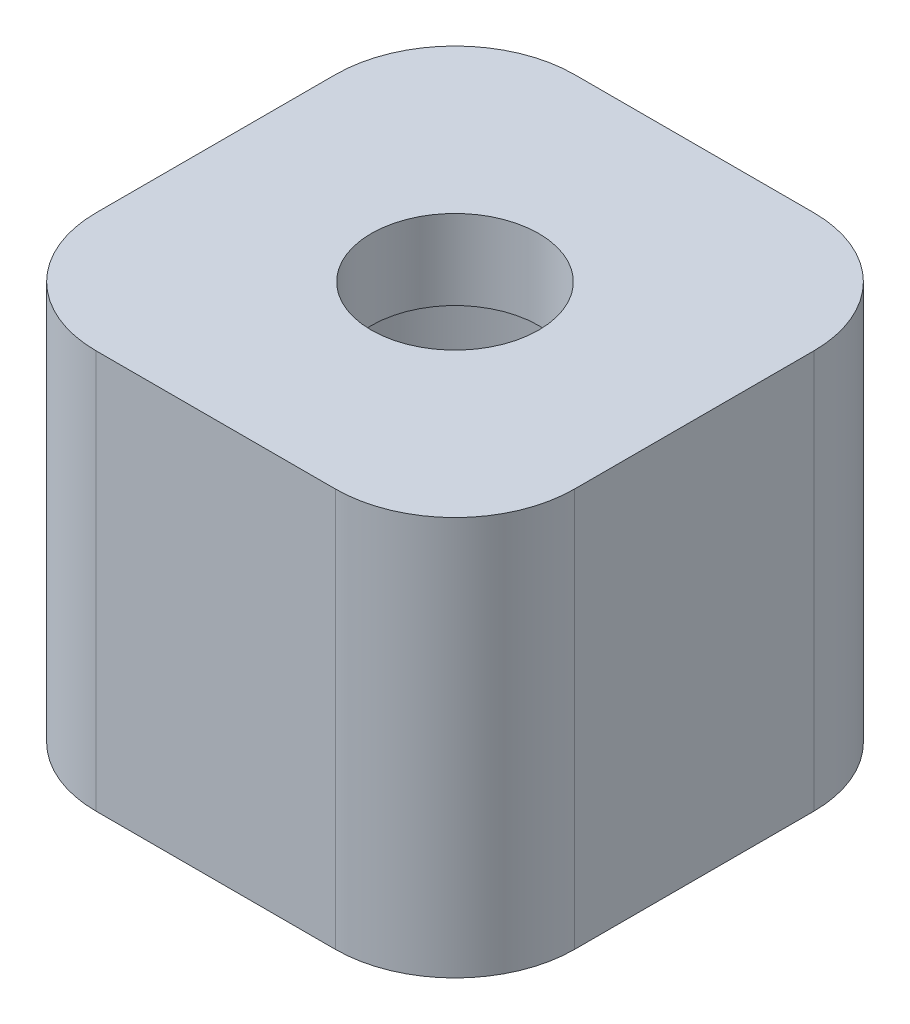
SolidWorks part; units mm, degrees
ref_plane "Спереди" through (0, 0, 0) normal (0, 0, 1) x (1, 0, 0)
ref_plane "Сверху" through (0, 0, 0) normal (0, 1, 0) x (1, 0, 0)
ref_plane "Справа" through (0, 0, 0) normal (1, 0, 0) x (0, 0, -1)
other "Configuration Table"
sketch "Sketch1" plane through (0, 0, 0) normal (0, 1, 0) x (1, 0, 0)
  line L1 (-3, -6) -> (3, -6)
  line L2 (-6, -3) -> (-6, 3)
  line L3 (-3, 6) -> (3, 6)
  line L4 (6, -3) -> (6, 3)
  line L5 (-6, -6) -> (6, 6) construction
  line L6 (-6, 6) -> (6, -6) construction
  circle A0 centre (0, 0) radius 2.1
  arc A1 (6, -3) -> (3, -6) centre (3, -3) cw
  arc A2 (-3, -6) -> (-6, -3) centre (-3, -3) cw
  arc A3 (-6, 3) -> (-3, 6) centre (-3, 3) cw
  arc A4 (3, 6) -> (6, 3) centre (3, 3) cw
  point P0 (0, 0)
  dimension "D2" = 4.2
  dimension "D3" = 3
  dimension "D1" = 12
extrude "Boss-Extrude1" add sketch "Sketch1" along normal blind 10
sketch "Sketch2" plane through (0, 0, 0) normal (0, -1, 0) x (1, 0, 0)
  circle A0 centre (0, 0) radius 4.4
  dimension "D1" = 8.8
extrude "Cut-Extrude1" cut sketch "Sketch2" against normal blind 8
